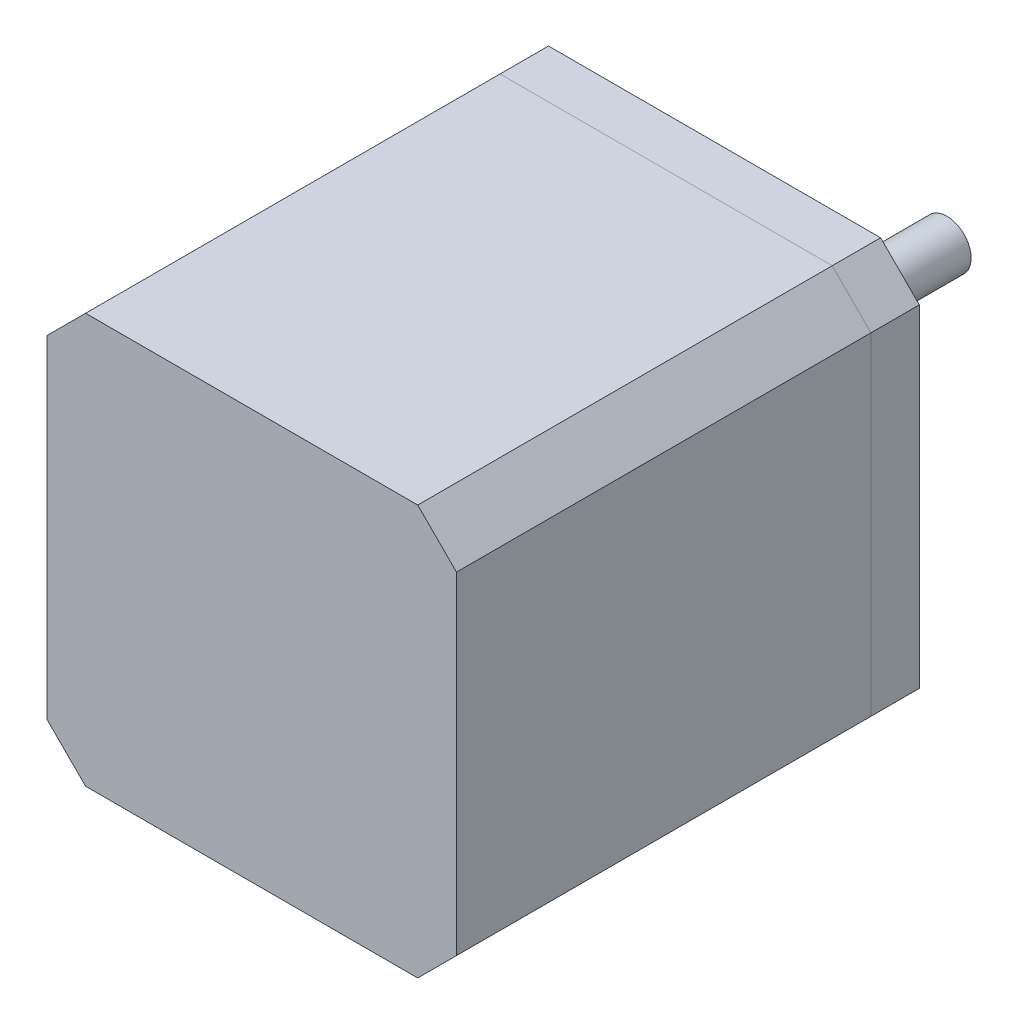
SolidWorks part; units mm, degrees
ref_plane "Спереди" through (0, 0, 0) normal (0, 0, 1) x (1, 0, 0)
ref_plane "Сверху" through (0, 0, 0) normal (0, 1, 0) x (1, 0, 0)
ref_plane "Справа" through (0, 0, 0) normal (1, 0, 0) x (0, 0, -1)
sketch "Эскиз1" plane through (0, 0, 0) normal (0, 0, -1) x (1, 0, 0)
  line L1 (0, 0) -> (42.3, 0)
  line L2 (0, 0) -> (0, 42.3)
  line L3 (0, 42.3) -> (42.3, 42.3)
  line L4 (42.3, 0) -> (42.3, 42.3)
  dimension "D1" = 42.3
extrude "front" add sketch "Эскиз1" along normal blind 5
chamfer "Фаска1" distance 4 angle 45 4 edges at (0, 0, -2.5) (42.3, 0, -2.5) (42.3, -42.3, -2.5) (0, -42.3, -2.5)
sketch "Эскиз2" plane through (0, 0, -5) normal (0, 0, -1) x (1, 0, 0)
  line L0 (21.15, 42.3) -> (21.15, 0) construction
  line L1 (38.3, 42.3) -> (4, 42.3) construction
  line L2 (4, 0) -> (38.3, 0) construction
  circle A0 centre (21.15, 21.15) radius 11
  point P8 (21.15, 21.15)
  dimension "D1" = 22
extrude "Вытянуть2" add sketch "Эскиз2" along normal blind 2
sketch "Эскиз3" plane through (0, 0, -7) normal (0, 0, -1) x (1, 0, 0)
  circle A0 centre (21.15, 21.15) radius 2.5
  circle A1 centre (21.15, 21.15) radius 11 construction
  dimension "D1" = 5
extrude "shaft" add sketch "Эскиз3" along normal blind 22
sketch "Эскиз4" plane through (0, 0, -29) normal (0, 0, -1) x (1, 0, 0)
  line L0 (19.15, 22.65) -> (19.15, 19.65)
  line L1 (23.65, 21.15) -> (18.65, 21.15) construction
  circle A0 centre (21.15, 21.15) radius 2.5 construction
  arc A1 (19.15, 22.65) -> (19.15, 19.65) centre (21.15, 21.15) ccw
  dimension "D1" = 4.5
extrude "slot" cut sketch "Эскиз4" against normal blind 15
sketch "Эскиз5" plane through (0, 0, -5) normal (0, 0, -1) x (-1, 0, 0)
  line L0 (-4, 0) -> (-38.3, 0) construction
  line L1 (-42.3, -4) -> (-42.3, -38.3) construction
  line L2 (-21.15, 0) -> (-21.15, -42.3) construction
  line L3 (-38.3, -42.3) -> (-4, -42.3) construction
  line L4 (-42.3, -21.15) -> (0, -21.15) construction
  line L5 (0, -38.3) -> (0, -4) construction
  circle A0 centre (-36.8, -5.5) radius 1.25
  circle A1 centre (-5.5, -5.5) radius 1.25
  circle A2 centre (-5.5, -36.8) radius 1.25
  circle A3 centre (-36.8, -36.8) radius 1.25
  dimension "D1" = 2.5
  dimension "D2" = 5.5
  dimension "D3" = 5.5
extrude "holes" cut sketch "Эскиз5" against normal blind 4
sketch "Эскиз6" plane through (0, 0, 0) normal (0, 0, 1) x (1, 0, 0)
  line L0 (0, -4) -> (4, 0)
  line L1 (4, 0) -> (38.3, 0)
  line L2 (38.3, 0) -> (42.3, -4)
  line L3 (42.3, -4) -> (42.3, -38.3)
  line L4 (42.3, -38.3) -> (38.3, -42.3)
  line L5 (38.3, -42.3) -> (4, -42.3)
  line L6 (4, -42.3) -> (0, -38.3)
  line L7 (0, -38.3) -> (0, -4)
extrude "body" add sketch "Эскиз6" along normal blind 42.8 separate body
